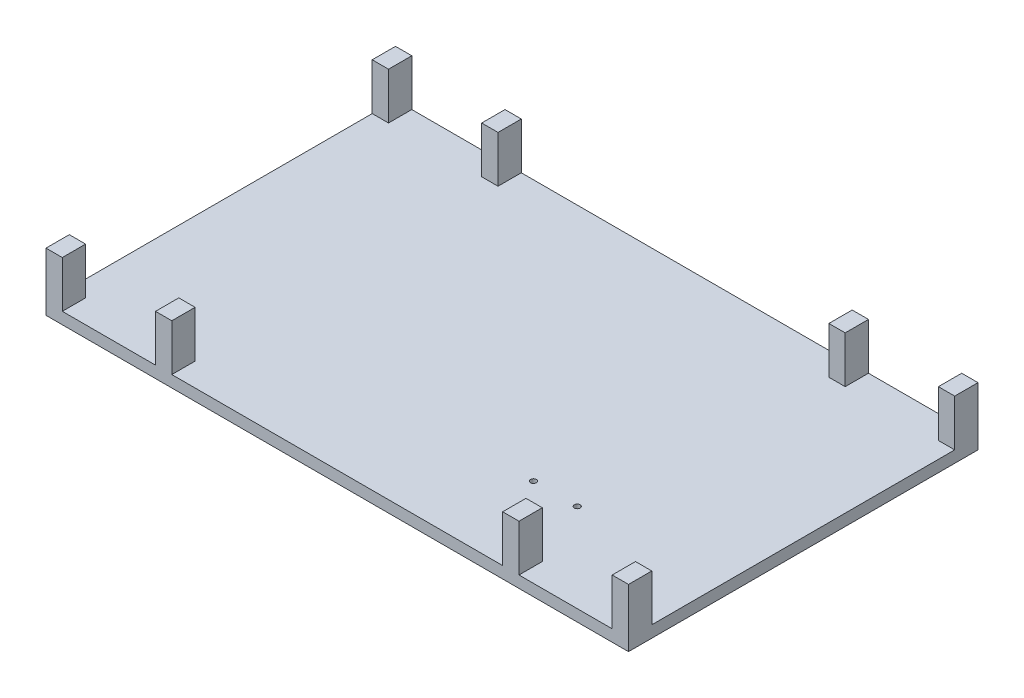
SolidWorks part; units mm, degrees
ref_plane "Front Plane" through (0, 0, 0) normal (0, 0, 1) x (1, 0, 0)
ref_plane "Top Plane" through (0, 0, 0) normal (0, 1, 0) x (1, 0, 0)
ref_plane "Right Plane" through (0, 0, 0) normal (1, 0, 0) x (0, 0, -1)
sketch "Sketch1" plane through (0, 0, 0) normal (0, 1, 0) x (1, 0, 0)
  line L1 (125, 75) -> (-125, 75)
  line L2 (125, 75) -> (125, -75)
  line L3 (125, -75) -> (-125, -75)
  line L4 (-125, 75) -> (-125, -75)
  line L5 (125, 75) -> (-125, -75) construction
  line L6 (125, -75) -> (-125, 75) construction
  point P1 (0, 0)
  dimension "D1" = 250
  dimension "D2" = 150
extrude "Boss-Extrude1" add sketch "Sketch1" along normal blind 5
sketch "Sketch2" plane through (0, 5, 0) normal (0, 1, 0) x (1, 0, 0)
  line L0 (-125, -75) -> (125, -75) construction
  line L1 (-125, -75) -> (-118, -75)
  line L2 (-125, -75) -> (-125, -65)
  line L3 (-125, -65) -> (-118, -65)
  line L4 (-118, -75) -> (-118, -65)
  line L5 (-78, -75) -> (-71, -75)
  line L6 (-78, -75) -> (-78, -65)
  line L7 (-78, -65) -> (-71, -65)
  line L8 (-71, -75) -> (-71, -65)
  line L9 (125, 75) -> (-125, 75) construction
  line L10 (-125, 75) -> (-118, 75)
  line L11 (-125, 75) -> (-125, 65)
  line L12 (-125, 65) -> (-118, 65)
  line L13 (-118, 75) -> (-118, 65)
  line L14 (-78, 75) -> (-71, 75)
  line L15 (-78, 75) -> (-78, 65)
  line L16 (-78, 65) -> (-71, 65)
  line L17 (-71, 75) -> (-71, 65)
  line L19 (125, 75) -> (118, 75)
  line L20 (125, 75) -> (125, 65)
  line L21 (125, 65) -> (118, 65)
  line L22 (118, 75) -> (118, 65)
  line L23 (78, 75) -> (71, 75)
  line L24 (78, 75) -> (78, 65)
  line L25 (78, 65) -> (71, 65)
  line L26 (71, 75) -> (71, 65)
  line L27 (125, -75) -> (118, -75)
  line L28 (125, -75) -> (125, -65)
  line L29 (125, -65) -> (118, -65)
  line L30 (118, -75) -> (118, -65)
  line L31 (78, -75) -> (71, -75)
  line L32 (78, -75) -> (78, -65)
  line L33 (78, -65) -> (71, -65)
  line L34 (71, -75) -> (71, -65)
  dimension "D1" = 7
  dimension "D2" = 10
  dimension "D3" = 40
  dimension "D4" = 40
  dimension "D5" = 40
  dimension "D6" = 40
extrude "Boss-Extrude2" add sketch "Sketch2" along normal blind 20
sketch "Sketch3" plane through (0, 5, 0) normal (0, 1, 0) x (1, 0, 0)
  line L0 (125, -65) -> (125, 65) construction
  line L1 (78, -75) -> (118, -75) construction
  circle A0 centre (46.2, -37) radius 1.25
  circle A1 centre (65, -37) radius 1.25
  dimension "D2" = 2.5
  dimension "D3" = 60
  dimension "D1" = 18.8
  dimension "D4" = 38
extrude "Cut-Extrude1" cut sketch "Sketch3" against normal through all
